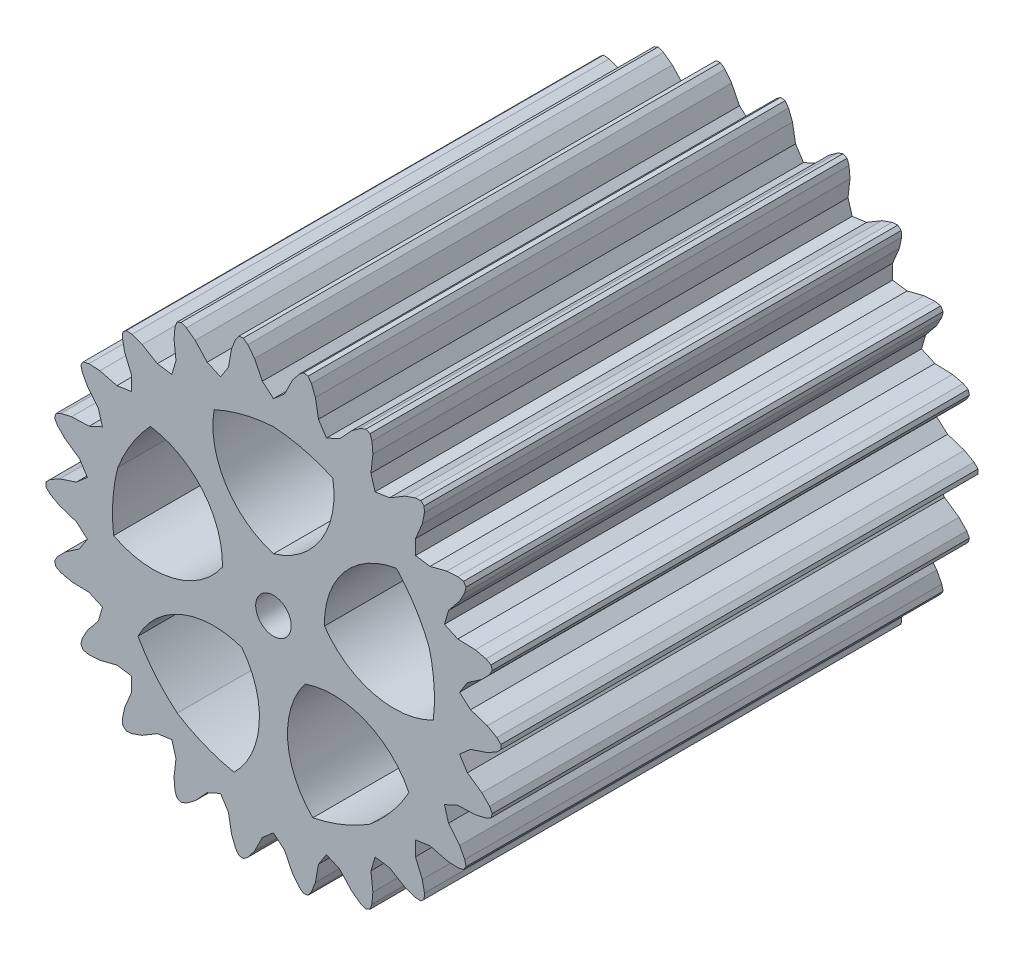
SolidWorks part; units mm, degrees
ref_plane "Front Plane" through (0, 0, 0) normal (0, 0, 1) x (1, 0, 0)
ref_plane "Top Plane" through (0, 0, 0) normal (0, 1, 0) x (1, 0, 0)
ref_plane "Right Plane" through (0, 0, 0) normal (1, 0, 0) x (0, 0, -1)
sketch "Sketch1" plane through (0, 0, 0) normal (0, 0, 1) x (1, 0, 0)
  line L1 (1.2374, -1.2374) -> (-1.2374, -1.2374) construction
  line L2 (1.2374, -1.2374) -> (1.2374, 1.2374) construction
  line L3 (1.2374, 1.2374) -> (-1.2374, 1.2374) construction
  line L4 (-1.2374, -1.2374) -> (-1.2374, 1.2374) construction
  line L5 (1.2374, -1.2374) -> (-1.2374, 1.2374) construction
  line L6 (1.2374, 1.2374) -> (-1.2374, -1.2374) construction
  circle A0 centre (0, 0) radius 20.5
  circle A1 centre (0, 0) radius 1.75 construction
  dimension "D1" = 41
  dimension "D2" = 3.5
extrude "Boss-Extrude1" add sketch "Sketch1" along normal blind 43
sketch "Sketch2" plane through (0, 0, 0) normal (0, 0, 1) x (1, 0, 0)
  line L0 (0, 0) -> (0, 10.088) construction
  line L1 (0, 16.9447) -> (-0.9985, 17.8041)
  line L8 (-2.7154, 20.3194) -> (0, 24.5037)
  line L11 (-0.9985, 17.8041) -> (-1.7043, 19.2252)
  line L12 (-1.7043, 19.2252) -> (-2.3066, 20.0063)
  line L13 (-2.3066, 20.0063) -> (-2.7154, 20.3194)
  line L14 (2.3066, 20.0063) -> (2.7154, 20.3194)
  line L15 (1.7043, 19.2252) -> (2.3066, 20.0063)
  line L16 (0.9985, 17.8041) -> (1.7043, 19.2252)
  line L17 (2.7154, 20.3194) -> (0, 24.5037)
  line L18 (0, 16.9447) -> (0.9985, 17.8041)
  circle A14 centre (0, 0) radius 20.5 construction
  point P4 (-1.9178, 20.4101)
  point P16 (0, 20.5)
  point P17 (-1.605, 20.0783)
  point P18 (-1.1019, 19.2915)
  point P19 (-0.6633, 18.2208)
  point P20 (0, 16.9447)
  point P21 (-0.8212, 17.7917)
  point P22 (-1.4914, 19.2531)
  point P23 (-2.0964, 20.0163)
  point P24 (-2.4798, 20.3495)
  point P25 (-0.9985, 17.8041)
  point P26 (-1.7043, 19.2252)
  point P27 (-2.3066, 20.0063)
  point P28 (-2.7154, 20.3194)
extrude "Cut-Extrude1" cut sketch "Sketch2" along normal through all
sketch "Sketch3" plane through (0, 0, 0) normal (0, 0, 1) x (1, 0, 0)
  circle A0 centre (0, 0) radius 7.5
  dimension "D1" = 15
sketch "Sketch4" plane through (0, 0, 43) normal (0, 0, 1) x (1, 0, 0)
  circle A0 centre (0, 0) radius 1.6
  dimension "D1" = 3.2
extrude "Cut-Extrude2" cut sketch "Sketch4" against normal through all both and the other way through all
pattern_circular "CirPattern1" count 22 over 360 about axis through (0, 0, 0) along (0, 0, 1) of "Cut-Extrude1"
sketch "Sketch5" plane through (0, 0, 0) normal (0, 0, 1) x (1, 0, 0)
  line L0 (0, 0) -> (0, 16.5734) construction
  arc A0 (0, 4.8339) -> (-5.3518, 13.4083) centre (2.1591, 12.139) cw
  arc A1 (-5.3518, 13.4083) -> (0, 14.7545) centre (0.9488, -0.3284) cw
  arc A2 (5.3518, 13.4083) -> (0, 14.7545) centre (-0.9488, -0.3284) ccw
  arc A3 (0, 4.8339) -> (5.3518, 13.4083) centre (-2.1591, 12.139) ccw
  point P7 (0, 14.9621)
  point P12 (5.3518, 13.4083)
extrude "Cut-Extrude4" cut sketch "Sketch5" along normal through all both and the other way through all
pattern_circular "CirPattern2" count 5 over 360 about axis through (0, 0, 0) along (0, 0, 1) of "Cut-Extrude4"
equation "\"circle\"=41"
equation "\"D1@Sketch1\"=\"circle\""
equation "\"separator_width\"=45"
equation "\"big-gear-thiccness\"=2"
equation "\"D1@Boss-Extrude1\"=\"separator_width\" - \"big-gear-thiccness\""
